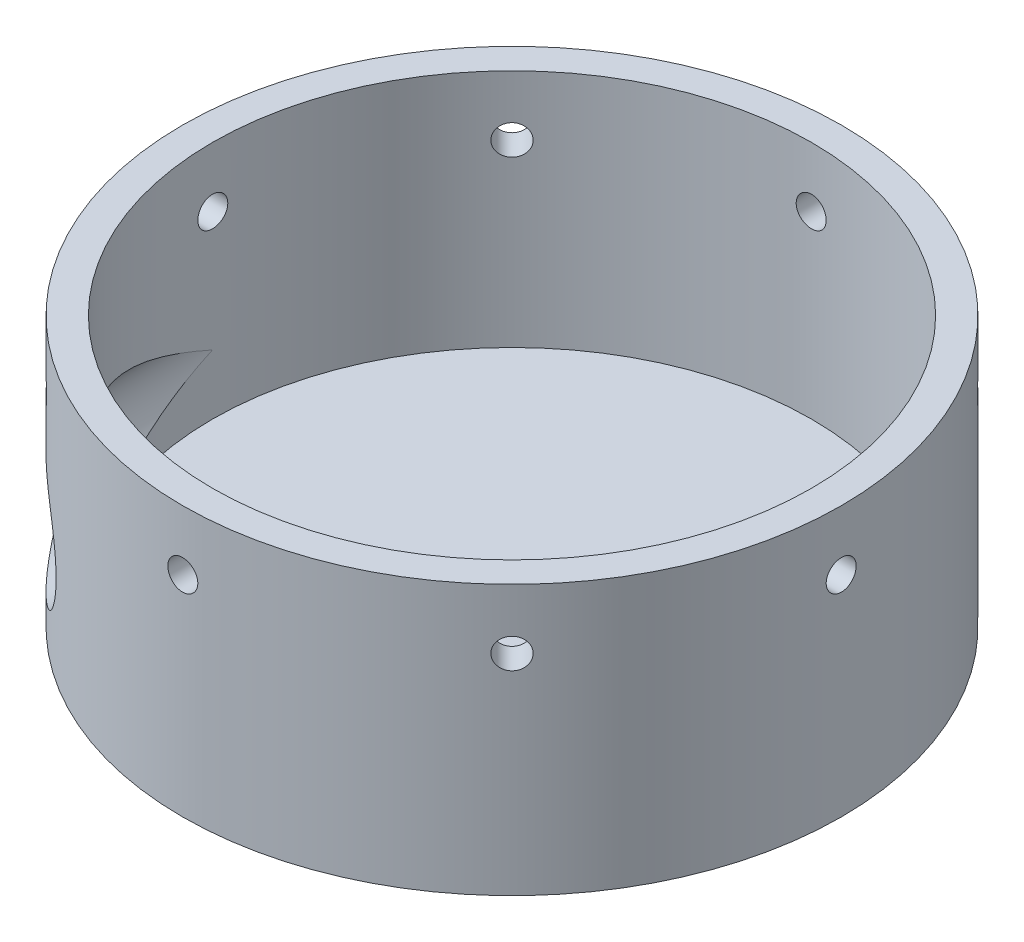
SolidWorks part; units mm, degrees
material "6061 Alloy"
ref_plane "Front Plane" through (0, 0, 0) normal (0, 0, 1) x (1, 0, 0)
ref_plane "Top Plane" through (0, 0, 0) normal (0, 1, 0) x (1, 0, 0)
ref_plane "Right Plane" through (0, 0, 0) normal (1, 0, 0) x (0, 0, -1)
sketch "Sketch1" plane through (0, 0, 0) normal (0, 0, 1) x (1, 0, 0)
  line L0 (6.35, 0) -> (6.35, 6.35)
  line L1 (6.35, 6.35) -> (63.5, 6.35)
  line L2 (63.5, 6.35) -> (63.5, 57.15)
  line L3 (63.5, 57.15) -> (69.85, 57.15)
  line L4 (69.85, 57.15) -> (69.85, 0)
  line L5 (69.85, 0) -> (6.35, 0)
  line L6 (0, 0) -> (0, 17.4457) construction
  dimension "D1" = 57.15
  dimension "D2" = 6.35
  dimension "D3" = 6.35
  dimension "D4" = 50.8
  dimension "D5" = 6.35
revolve "Revolve1" add sketch "Sketch1" angle 360 about L6
sketch "Sketch2" plane through (0, 0, 0) normal (0, 0, 1) x (1, 0, 0)
  line L0 (0, 57.15) -> (0, 6.35) construction
  line L1 (63.5, 57.15) -> (-63.5, 57.15) construction
  circle A0 centre (0, 44.45) radius 3.175
  dimension "D2" = 6.35
  dimension "D1" = 12.7
extrude "Cut-Extrude1" cut sketch "Sketch2" against normal through all
pattern_circular "CirPattern1" count 8 over 360 about axis through (0, 0, 0) along (0, -1, 0) of "Cut-Extrude1"
sketch "Sketch3" plane through (0, 0, 0) normal (0, 0, 1) x (1, 0, 0)
  line L1 (-50.8, 19.05) -> (-50.8, 0) construction
  line L4 (-63.5, 19.05) -> (-69.85, 19.05) construction
  line L5 (-69.85, 41.275) -> (-69.85, 0) construction
  line L6 (-69.85, 0) -> (69.85, 0) construction
  circle A0 centre (-50.8, 19.05) radius 12.7
  dimension "D1" = 25.4
  dimension "D2" = 6.35
  dimension "D3" = 19.05
extrude "Cut-Extrude2" cut sketch "Sketch3" along normal through all
